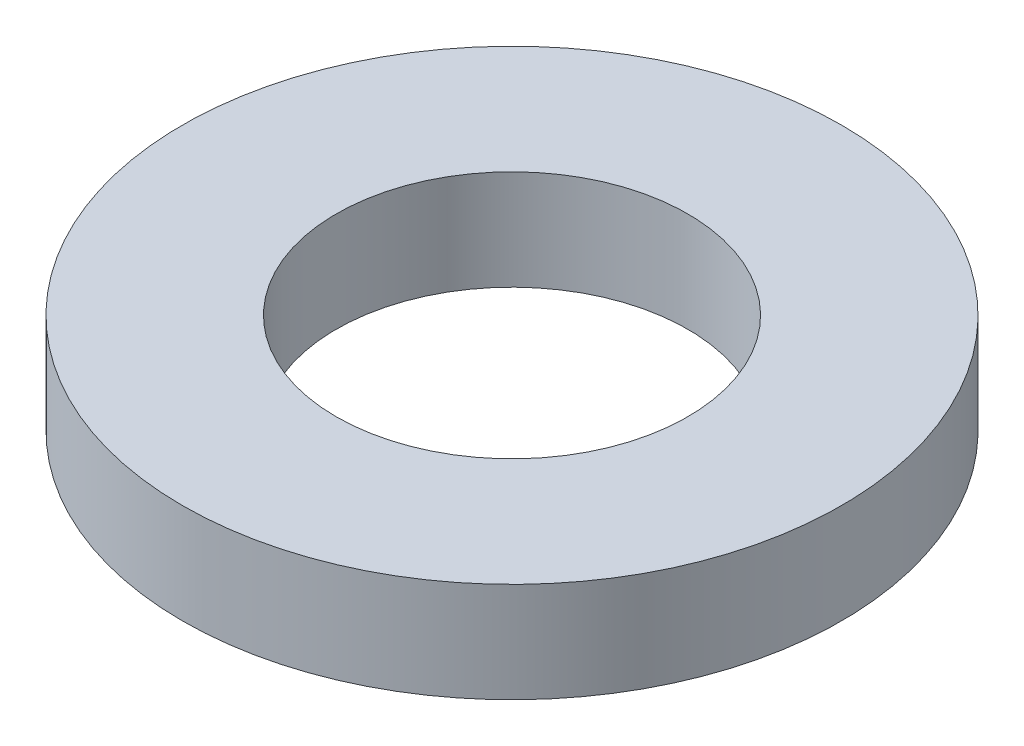
SolidWorks part; units mm, degrees
material "Plain Carbon Steel"
ref_plane "Front Plane" through (0, 0, 0) normal (0, 0, 1) x (1, 0, 0)
ref_plane "Top Plane" through (0, 0, 0) normal (0, 1, 0) x (1, 0, 0)
ref_plane "Right Plane" through (0, 0, 0) normal (1, 0, 0) x (0, 0, -1)
sketch "Sketch1" plane through (0, 0, 0) normal (0, 1, 0) x (1, 0, 0)
  circle A0 centre (0, 0) radius 11.9062
  circle A1 centre (0, 0) radius 6.35
  dimension "D1" = 23.8125
  dimension "D2" = 12.7
extrude "Boss-Extrude1" add sketch "Sketch1" along normal blind 3.61
